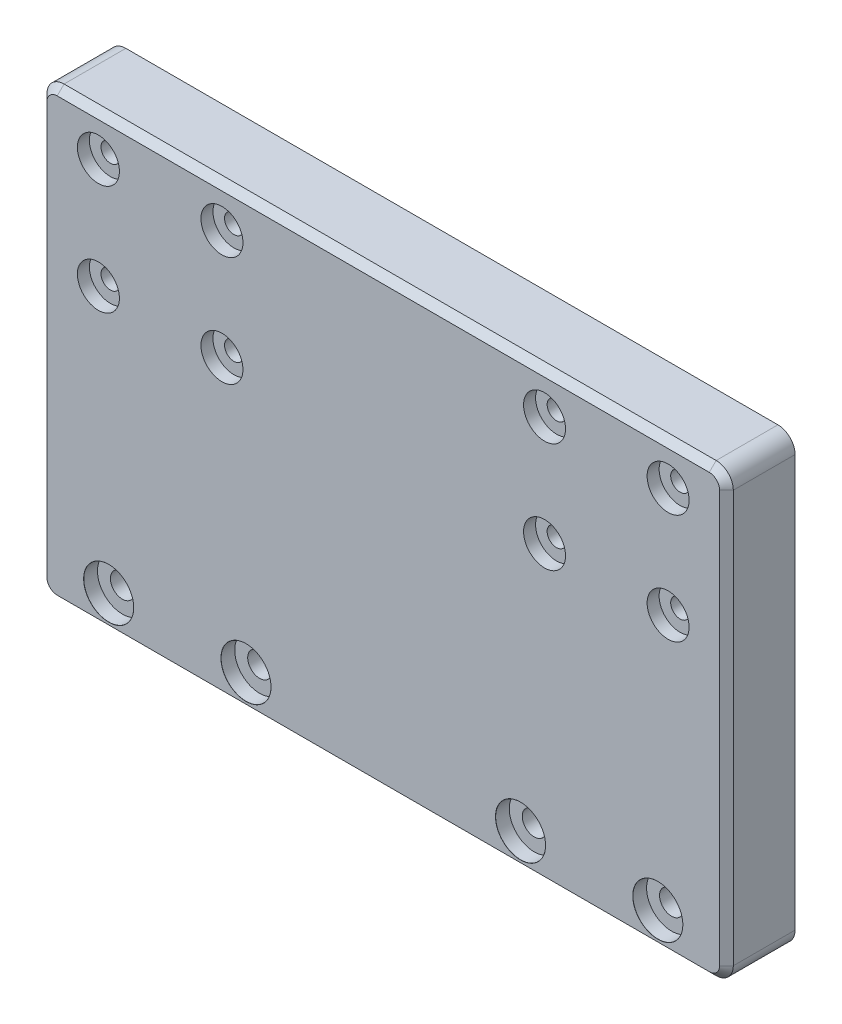
SolidWorks part; units mm, degrees
ref_plane "Front Plane" through (0, 0, 0) normal (0, 0, 1) x (1, 0, 0)
ref_plane "Top Plane" through (0, 0, 0) normal (0, 1, 0) x (1, 0, 0)
ref_plane "Right Plane" through (0, 0, 0) normal (1, 0, 0) x (0, 0, -1)
sketch "Sketch1" plane through (0, 0, 0) normal (0, 0, 1) x (1, 0, 0)
  line L1 (0, 0) -> (200, 0)
  line L2 (0, 0) -> (0, 130)
  line L3 (0, 130) -> (200, 130)
  line L4 (200, 0) -> (200, 130)
  dimension "D1" = 130
  dimension "D2" = 200
extrude "Boss-Extrude1" add sketch "Sketch1" along normal blind 20
fillet "Fillet1" radius 5 4 edges at (200, 130, 10) (200, 0, 10) (0, 0, 10) (0, 130, 10)
hole_wizard "CBORE for M6 Hex Head Bolt2" positions "Sketch16" profile "Sketch17" counterbore size "M6" standard "DIN" end condition through all
sketch "Sketch16" plane through (0, 0, 20) normal (0, 0, 1) x (1, 0, 0)
  line L0 (0, 125) -> (0, 5) construction
  line L1 (200, 5) -> (200, 125) construction
  line L2 (5, 0) -> (195, 0) construction
  point P0 (20, 10)
  point P2 (60, 10)
  point P4 (140, 10)
  point P6 (180, 10)
  dimension "D1" = 20
  dimension "D2" = 60
  dimension "D3" = 20
  dimension "D4" = 60
  dimension "D8" = 10
sketch "Sketch17" plane through (20, 10, 20) normal (1, 0, 0) x (0, -1, 0)
  line L0 (0, 0) -> (0, 20)
  line L1 (0, 20) -> (3.5, 20)
  line L3 (3.5, 20) -> (3.5, 4)
  line L4 (7.2735, 4) -> (3.5, 4)
  line L5 (7.2735, 4) -> (7.2735, 0.025)
  line L6 (7.2735, 0.025) -> (7.2985, 0)
  line L7 (7.2985, 0) -> (0, 0)
  line L8 (-7.2735, 0.025) -> (-7.2985, 0) construction
  line L11 (0, -6.35) -> (0, 107.95) construction
  dimension "Thru Hole Dia." = 7
  dimension "Thru Hole Depth" = 20
  dimension "C'Bore Dia." = 14.547
  dimension "C'Bore Depth" = 4
  dimension "Near C'Sink Dia." = 14.597
  dimension "Near C'Sink Angle" = 90
hole_wizard "CBORE for M5 Hex Head Bolt1" positions "Sketch20" profile "Sketch21" counterbore size "M5" standard "DIN" end condition through all
sketch "Sketch20" plane through (0, 0, 20) normal (0, 0, 1) x (1, 0, 0)
  line L0 (195, 130) -> (5, 130) construction
  line L1 (0, 125) -> (0, 5) construction
  line L2 (200, 5) -> (200, 125) construction
  point P0 (17, 118)
  point P7 (53, 118)
  point P9 (53, 86)
  point P11 (17, 86)
  point P16 (183, 118)
  point P18 (183, 86)
  point P20 (147, 118)
  point P22 (147, 86)
  dimension "D1" = 12
  dimension "D2" = 17
  dimension "D3" = 32
  dimension "D4" = 36
  dimension "D5" = 12
  dimension "D6" = 32
  dimension "D7" = 36
  dimension "D8" = 12
  dimension "D9" = 32
  dimension "D10" = 17
  dimension "D11" = 36
  dimension "D12" = 17
  dimension "D13" = 36
  dimension "D14" = 32
  dimension "D15" = 12
sketch "Sketch21" plane through (17, 118, 20) normal (1, 0, 0) x (0, -1, 0)
  line L0 (0, 0) -> (0, 20)
  line L1 (0, 20) -> (2.75, 20)
  line L3 (2.75, 20) -> (2.75, 3.5)
  line L4 (2.75, 3.5) -> (6.119, 3.5)
  line L5 (6.119, 3.5) -> (6.119, 0)
  line L7 (6.119, 0) -> (0, 0)
  line L11 (0, -6.35) -> (0, 107.95) construction
  dimension "Thru Hole Dia." = 5.5
  dimension "Thru Hole Depth" = 20
  dimension "C'Bore Dia." = 12.238
  dimension "C'Bore Depth" = 3.5
chamfer "Chamfer1" distance 2 angle 45 8 edges at (100, 0, 20) (198.5355, 1.4645, 20) (1.4645, 1.4645, 20) (200, 65, 20) (0, 65, 20) (198.5355, 128.5355, 20) (1.4645, 128.5355, 20) (100, 130, 20)
